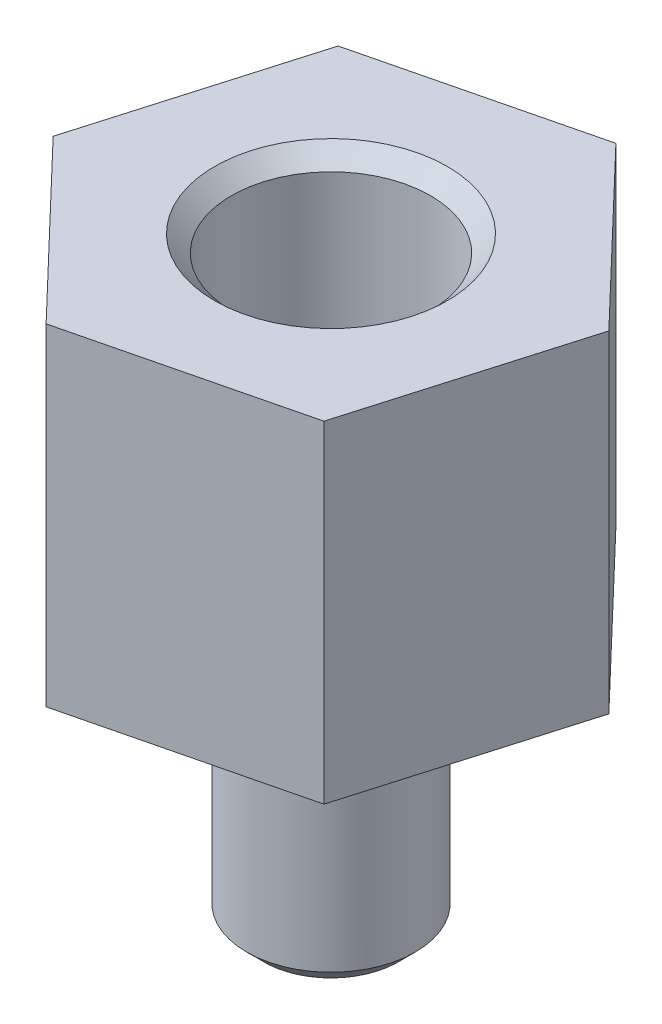
SolidWorks part; units mm, degrees
material "Nylon 101"
ref_plane "Front Plane" through (0, 0, 0) normal (0, 0, 1) x (1, 0, 0)
ref_plane "Top Plane" through (0, 0, 0) normal (0, 1, 0) x (1, 0, 0)
ref_plane "Right Plane" through (0, 0, 0) normal (1, 0, 0) x (0, 0, -1)
sketch "Sketch1" plane through (0, 0, 0) normal (0, 1, 0) x (1, 0, 0)
  line L1 (2.3957, -2.5021) -> (3.3648, 0.8236)
  line L2 (3.3648, 0.8236) -> (0.9691, 3.3258)
  line L3 (0.9691, 3.3258) -> (-2.3957, 2.5021)
  line L4 (-2.3957, 2.5021) -> (-3.3648, -0.8236)
  line L5 (-3.3648, -0.8236) -> (-0.9691, -3.3258)
  line L6 (-0.9691, -3.3258) -> (2.3957, -2.5021)
  circle A0 centre (0, 0) radius 3 construction
  dimension "D1" = 6
extrude "Boss-Extrude1" add sketch "Sketch1" along normal blind 5
sketch "Sketch2" plane through (0, 5, 0) normal (0, 1, 0) x (1, 0, 0)
  circle A0 centre (0, 0) radius 1.5
  dimension "D1" = 3
extrude "Cut-Extrude1" cut sketch "Sketch2" against normal blind 4
sketch "Sketch3" plane through (0, 0, 0) normal (0, -1, 0) x (1, 0, 0)
  circle A0 centre (0, 0) radius 1.27
  dimension "D1" = 2.54
extrude "Boss-Extrude2" add sketch "Sketch3" along normal blind 4
chamfer "Chamfer1" distance 0.254 angle 45 1 edges at (0, -4, -1.27)
chamfer "Chamfer2" distance 0.254 angle 45 1 edges at (0, 5, 1.5)
